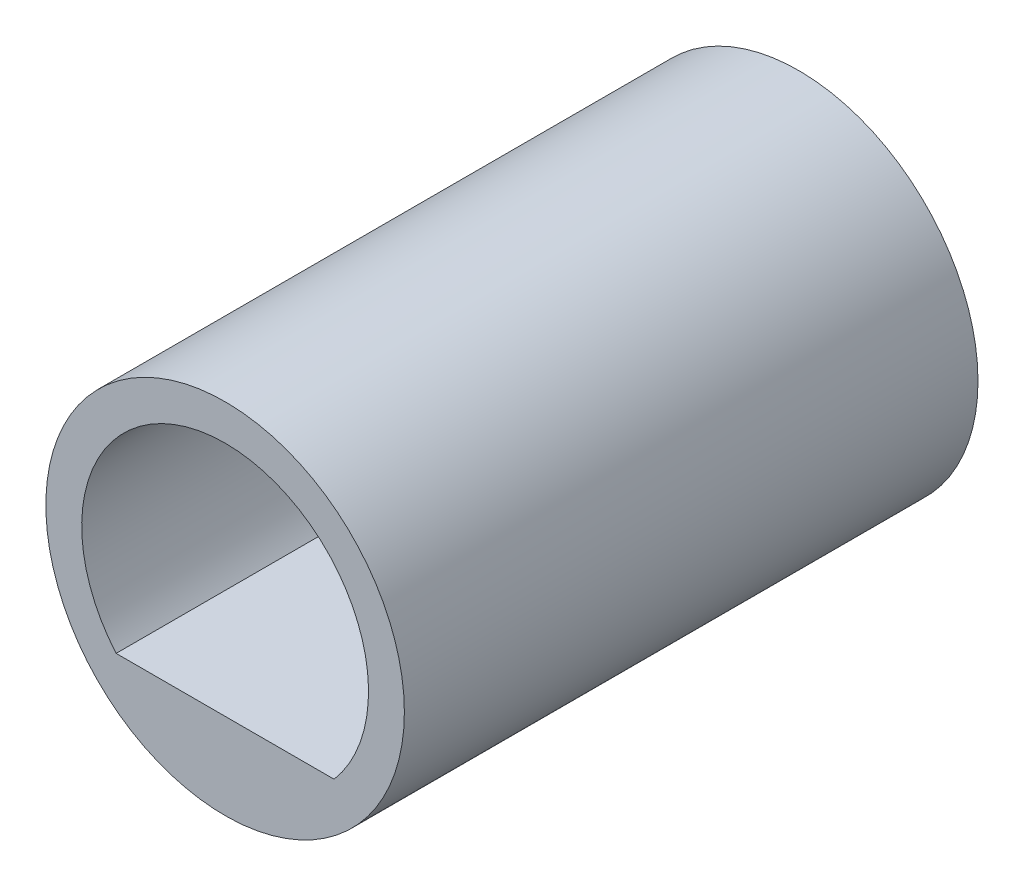
SolidWorks part; units mm, degrees
ref_plane "Ön Düzlem" through (0, 0, 0) normal (0, 0, 1) x (1, 0, 0)
ref_plane "Üst Düzlem" through (0, 0, 0) normal (0, 1, 0) x (1, 0, 0)
ref_plane "Sağ Düzlem" through (0, 0, 0) normal (1, 0, 0) x (0, 0, -1)
sketch "Çizim1" plane through (0, 0, 0) normal (0, 0, 1) x (1, 0, 0)
  line L1 (-1.5199, -1.3) -> (1.5199, -1.3)
  circle A0 centre (0, 0) radius 2.5
  arc A1 (1.5199, -1.3) -> (-1.5199, -1.3) centre (0, 0) ccw
  dimension "D1" = 5
  dimension "D2" = 4
extrude "Yükseklik-Ekstrüzyon1" add sketch "Çizim1" along normal blind 8
ref_plane "Düzlem1" through (0, -2.5, 0) normal (0, 1, 0) x (-1, 0, 0)
